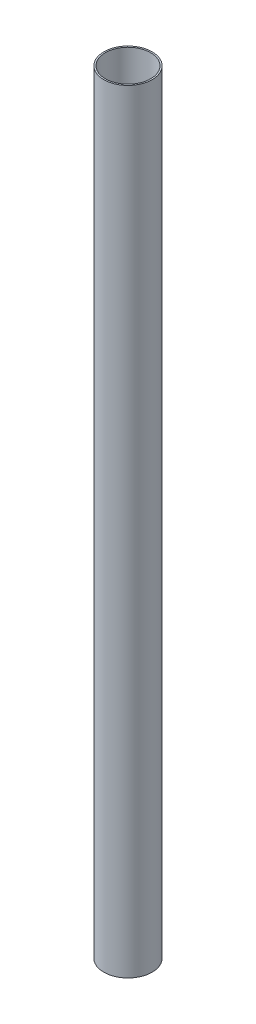
SolidWorks part; units mm, degrees
material "6061-T6 (SS)"
ref_plane "Front Plane" through (0, 0, 0) normal (0, 0, 1) x (1, 0, 0)
ref_plane "Top Plane" through (0, 0, 0) normal (0, 1, 0) x (1, 0, 0)
ref_plane "Right Plane" through (0, 0, 0) normal (1, 0, 0) x (0, 0, -1)
sketch "Sketch1" plane through (0, 0, 0) normal (0, 1, 0) x (1, 0, 0)
  circle A0 centre (0, 0) radius 25.4
  dimension "D1" = 50.8
extrude "Boss-Extrude1" add sketch "Sketch1" along normal mid plane 812.8
shell "Shell1" thickness 1.5875
